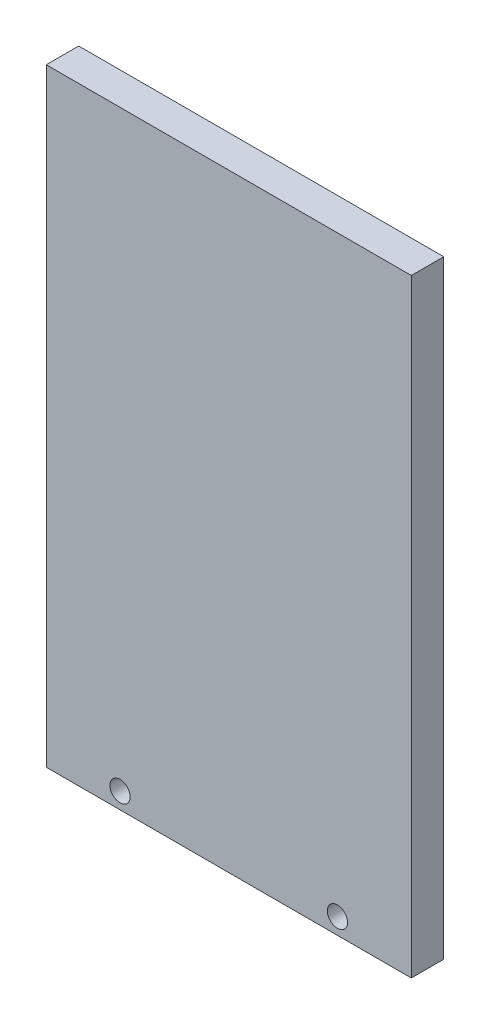
SolidWorks part; units mm, degrees
material "Aleación 1060"
ref_plane "Alzado" through (0, 0, 0) normal (0, 0, 1) x (1, 0, 0)
ref_plane "Planta" through (0, 0, 0) normal (0, 1, 0) x (1, 0, 0)
ref_plane "Vista lateral" through (0, 0, 0) normal (1, 0, 0) x (0, 0, -1)
sketch "Croquis1" plane through (0, 0, 0) normal (0, 0, 1) x (1, 0, 0)
  line L0 (-15, 24.3435) -> (30, 24.3435)
  line L1 (7.5, -18.4) -> (-15, -18.4) construction
  line L2 (-15, 24.3435) -> (-15, -50.6565)
  line L3 (7.5, -4) -> (7.5, -18.4) construction
  line L4 (30, 24.3435) -> (30, -50.6565)
  line L5 (-15, -50.6565) -> (30, -50.6565)
  line L6 (7.5, -50.6565) -> (7.5, -46.6565) construction
  line L7 (-10.9, -50.6565) -> (-10.9, -46.6565) construction
  circle A6 centre (-5.9, -48.6565) radius 1.25
  circle A7 centre (20.9, -48.6565) radius 1.25
  point P5 (7.5, -48.6565)
  dimension "D3" = 45
  dimension "D5" = 18.4
  dimension "D10" = 2.5
  dimension "D2" = 4
  dimension "D7" = 75
  dimension "D4" = 5
extrude "Saliente-Extruir1" add sketch "Croquis1" along normal blind 4
